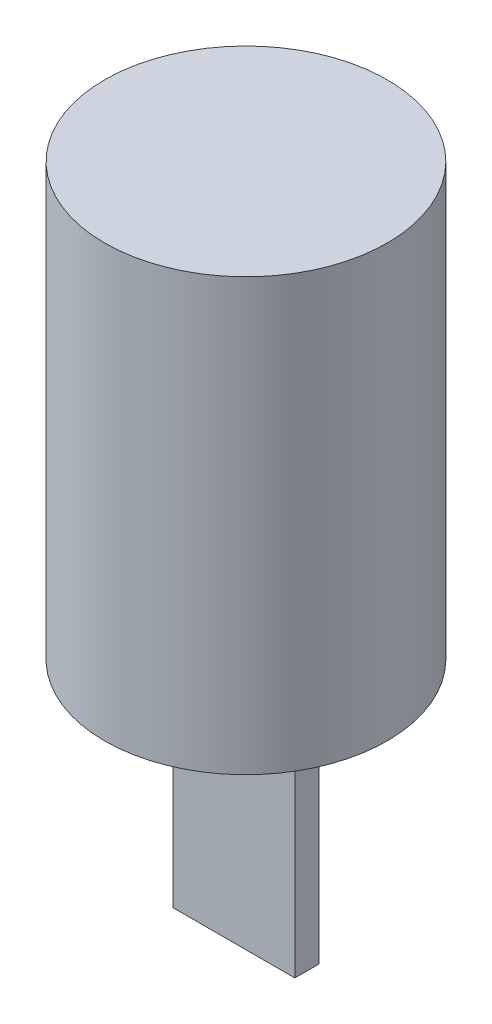
SolidWorks part; units mm, degrees
ref_plane "Front Plane" through (0, 0, 0) normal (0, 0, 1) x (1, 0, 0)
ref_plane "Top Plane" through (0, 0, 0) normal (0, 1, 0) x (1, 0, 0)
ref_plane "Right Plane" through (0, 0, 0) normal (1, 0, 0) x (0, 0, -1)
sketch "Sketch2" plane through (0, 0, 0) normal (0, 1, 0) x (1, 0, 0)
  circle A0 centre (0, 0) radius 2.95
  dimension "D1" = 5.9
extrude "Boss-Extrude1" add sketch "Sketch2" along normal blind 9
sketch "Sketch3" plane through (0, 0, 0) normal (0, -1, 0) x (1, 0, 0)
  line L1 (1.27, 0.25) -> (-1.27, 0.25)
  line L2 (1.27, 0.25) -> (1.27, -0.25)
  line L3 (1.27, -0.25) -> (-1.27, -0.25)
  line L4 (-1.27, 0.25) -> (-1.27, -0.25)
  dimension "D1" = 0.5
  dimension "D2" = 0.25
  dimension "D3" = 1.27
  dimension "D4" = 1.27
extrude "Boss-Extrude2" add sketch "Sketch3" along normal blind 5
equation "\"D4@Sketch3\"=\"D3@Sketch3\""
